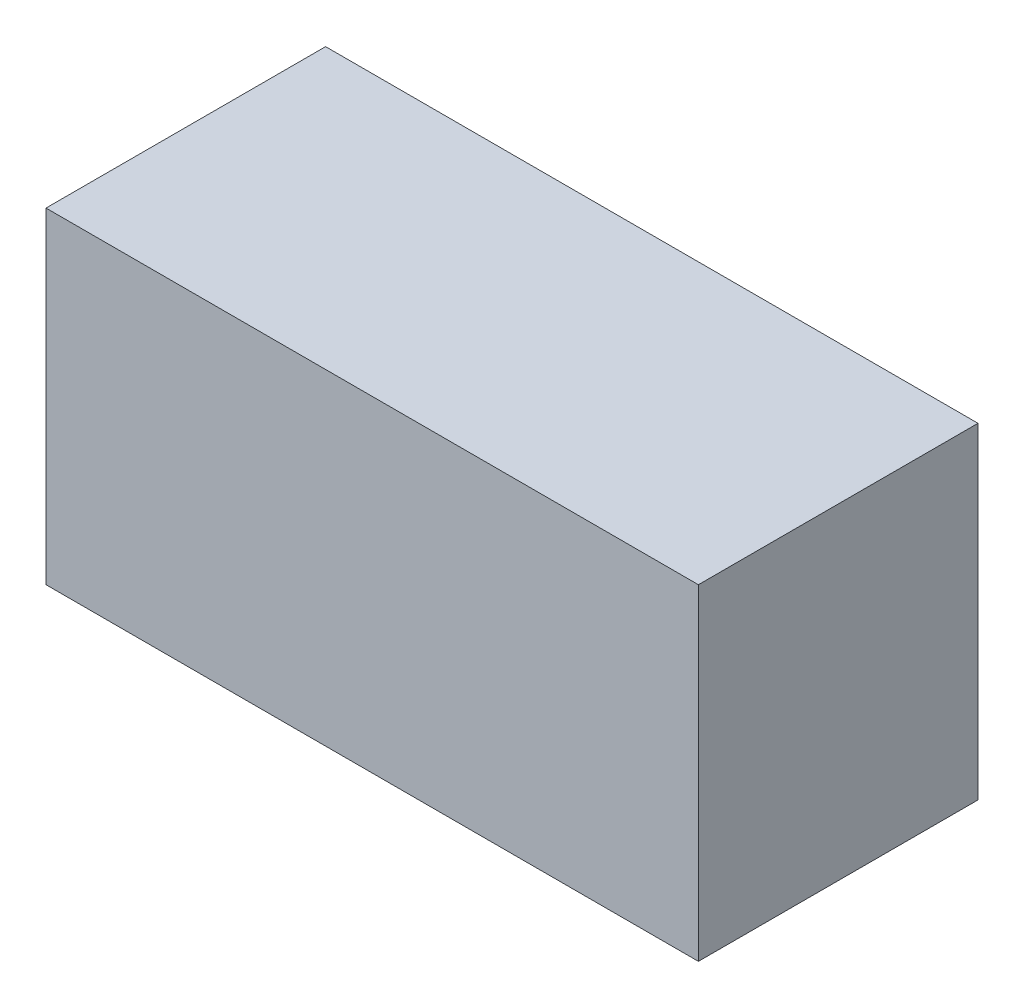
SolidWorks part; units mm, degrees
material "PA Tip 6"
ref_plane "Ön Düzlem" through (0, 0, 0) normal (0, 0, 1) x (1, 0, 0)
ref_plane "Üst Düzlem" through (0, 0, 0) normal (0, 1, 0) x (1, 0, 0)
ref_plane "Sağ Düzlem" through (0, 0, 0) normal (1, 0, 0) x (0, 0, -1)
sketch "Çizim1" plane through (0, 0, 0) normal (0, 0, 1) x (1, 0, 0)
  line L1 (0, 0) -> (140, 0)
  line L2 (0, 0) -> (0, 70)
  line L3 (0, 70) -> (140, 70)
  line L4 (140, 0) -> (140, 70)
  dimension "D1" = 70
  dimension "D2" = 140
extrude "Yükseklik-Ekstrüzyon1" add sketch "Çizim1" along normal blind 60
sketch "Çizim10" plane through (0, 0, 0) normal (0, -1, 0) x (1, 0, 0)
  line L0 (0, 60) -> (0, 0) construction
  line L1 (5, 55) -> (135, 55)
  line L2 (5, 55) -> (5, 5)
  line L3 (5, 5) -> (135, 5)
  line L4 (135, 55) -> (135, 5)
  line L6 (0, 60) -> (140, 60) construction
  dimension "D1" = 130
  dimension "D2" = 5
  dimension "D3" = 50
  dimension "D4" = 5
extrude "Kes-Ekstrüzyon6" cut sketch "Çizim10" against normal blind 65
sketch "Çizim12" plane through (0, 0, 0) normal (0, -1, 0) x (1, 0, 0)
  line L0 (5, 5) -> (135, 5) construction
  line L1 (5, 55) -> (40, 55)
  line L2 (5, 55) -> (5, 5)
  line L3 (5, 5) -> (40, 5)
  line L4 (40, 55) -> (40, 5)
  line L5 (5, 5) -> (135, 5) construction
  line L6 (135, 55) -> (100, 55)
  line L7 (135, 55) -> (135, 5)
  line L8 (135, 5) -> (100, 5)
  line L9 (100, 55) -> (100, 5)
  dimension "D1" = 35
  dimension "D2" = 35
extrude "Yükseklik-Ekstrüzyon3" add sketch "Çizim12" against normal blind 5
